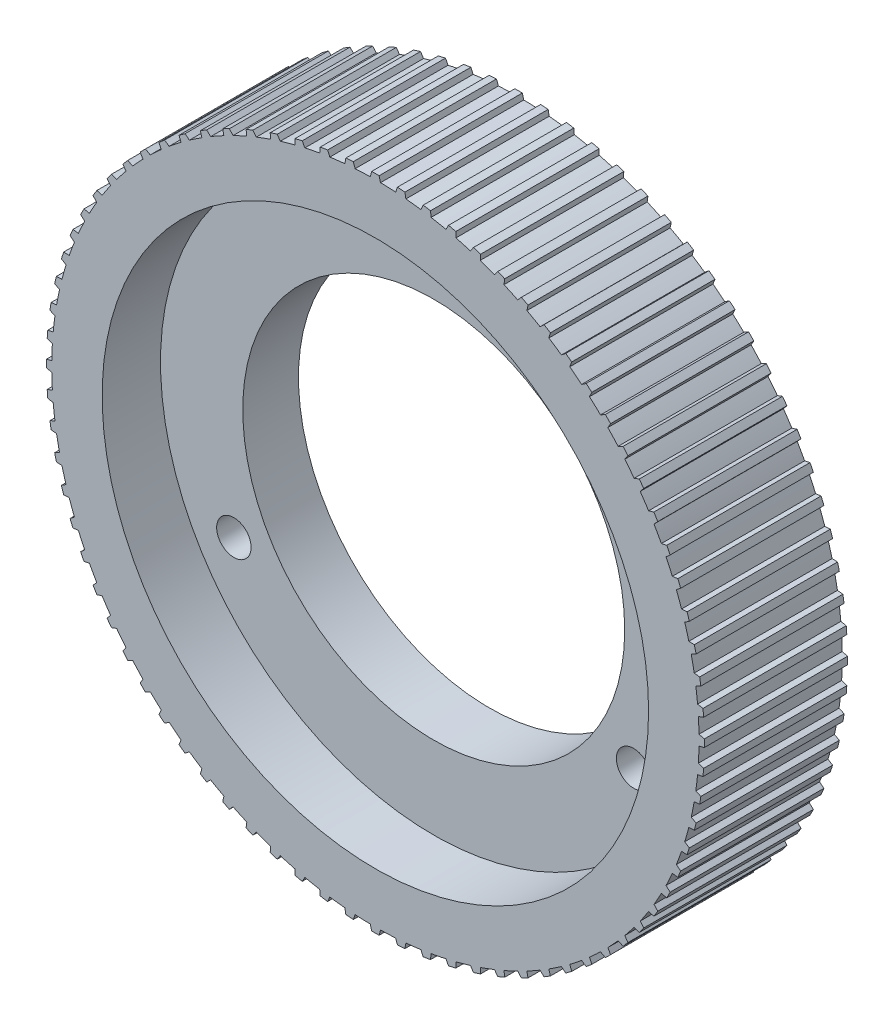
SolidWorks part; units mm, degrees
ref_plane "Face" through (0, 0, 0) normal (0, 0, 1) x (1, 0, 0)
ref_plane "Dessus" through (0, 0, 0) normal (0, 1, 0) x (1, 0, 0)
ref_plane "Droite" through (0, 0, 0) normal (1, 0, 0) x (0, 0, -1)
sketch "Esquisse1" plane through (0, 0, 0) normal (0, 0, 1) x (1, 0, 0)
  circle A0 centre (0, 0) radius 61.0024
  dimension "D1" = 122.0048
extrude "Base-Extrusion" add sketch "Esquisse1" against normal mid plane 27
sketch "Esquisse5" plane through (0, 0, 0) normal (0, 0, 1) x (1, 0, 0)
  line L0 (0.7021, 61.9984) -> (0.971, 60.9947)
  line L1 (-0.7021, 61.9984) -> (-0.971, 60.9947)
  line L8 (0, 61.5024) -> (0, 15.5499) construction
  arc A0 (0.7021, 61.9984) -> (-0.7021, 61.9984) centre (0, 0) ccw
  arc A1 (0.971, 60.9947) -> (-0.971, 60.9947) centre (0, 0) ccw
  arc A2 (-0.7021, 61.9984) -> (0.7021, 61.9984) centre (0, 0) ccw construction
  arc A3 (0.8365, 61.4967) -> (-0.8365, 61.4967) centre (0, 0) ccw construction
  circle A4 centre (0, 0) radius 61.0024 construction
  dimension "D7" = 123.0048
  dimension "D6" = 124.0048
  dimension "D2" = 1.673
  dimension "D1" = 15
extrude "Boss.-Extru.1" add sketch "Esquisse5" against normal up to surface and the other way up to surface up to face at (61.0024, 0, -13.5) other way up to face at (61.0024, 0, 13.5)
pattern_circular "Répétition circulaire1" count 80 over 360 about axis through (0, 0, 0) along (0, 0, 1) of "Boss.-Extru.1"
sketch "Esquisse6" plane through (0, 0, 13.5) normal (0, 0, 1) x (1, 0, 0)
  circle A0 centre (0, 0) radius 51.5
  dimension "D1" = 103
extrude "Enlèv. mat.-Extru.1" cut sketch "Esquisse6" against normal blind 11
sketch "Esquisse7" plane through (0, 0, 0) normal (0, 1, 0) x (1, 0, 0)
  line L0 (-49.25, 17.1187) -> (-49.25, 10.5)
  line L1 (-49.25, 10.5) -> (-48, 10.5)
  line L2 (-48, 10.5) -> (-48, 8)
  line L3 (-48, 8) -> (-36, 8)
  line L4 (0, -19.5436) -> (0, 17.1187)
  line L5 (0, 17.1187) -> (-49.25, 17.1187)
  line L6 (0, -44.3248) -> (0, 21.6039) construction
  line L7 (-36, 8) -> (-36, -19.5436)
  line L8 (-36, -19.5436) -> (0, -19.5436)
  dimension "D1" = 3
  dimension "D2" = 5.5
  dimension "D3" = 98.5
  dimension "D4" = 96
  dimension "D5" = 72
revolve "Enlèvement de matière-Révolution1" cut sketch "Esquisse7" angle 360 about L6
sketch "Esquisse8" plane through (0, 0, 2.5) normal (0, 0, 1) x (1, 0, 0)
  circle A0 centre (0, 43.5) radius 3.25
  dimension "D2" = 6.5
  dimension "D1" = 43.5
extrude "Enlèv. mat.-Extru.2" cut sketch "Esquisse8" against normal up to next
pattern_circular "Répétition circulaire2" count 3 every 120 about axis through (0, 0, 0) along (0, 0, 1) of "Enlèv. mat.-Extru.2"
